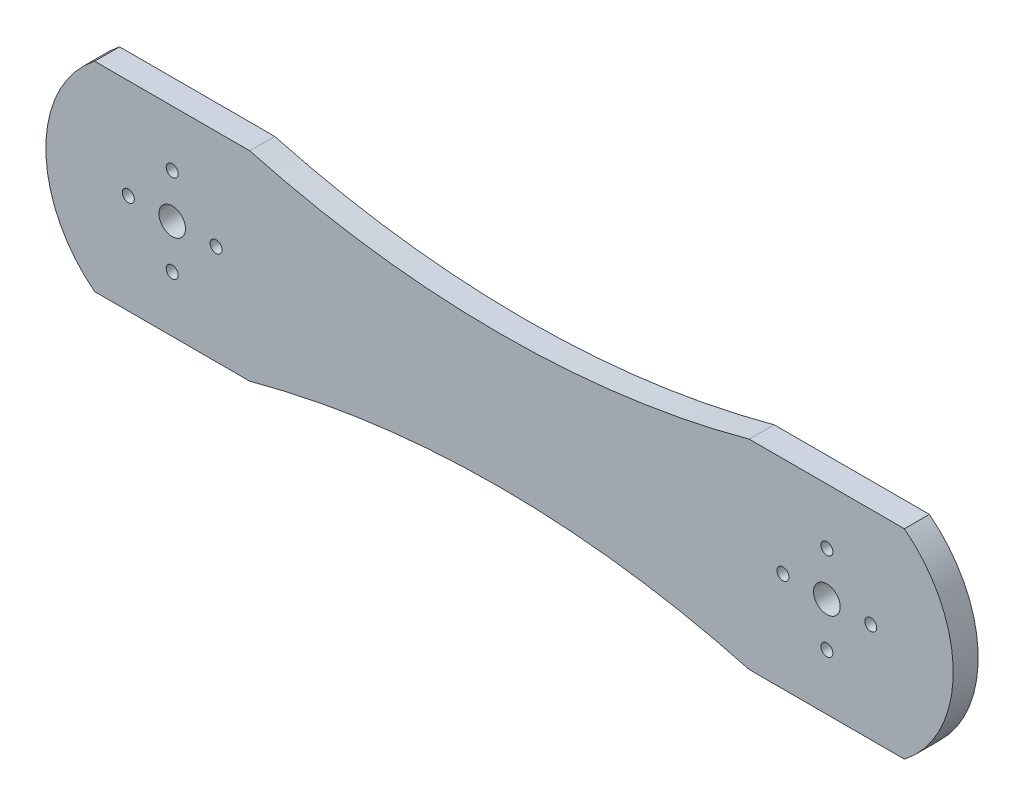
SolidWorks part; units mm, degrees
ref_plane "Front Plane" through (0, 0, 0) normal (0, 0, 1) x (1, 0, 0)
ref_plane "Top Plane" through (0, 0, 0) normal (0, 1, 0) x (1, 0, 0)
ref_plane "Right Plane" through (0, 0, 0) normal (1, 0, 0) x (0, 0, -1)
sketch "Sketch1" plane through (0, 0, 0) normal (0, 0, 1) x (1, 0, 0)
  line L0 (-77.3106, 19.05) -> (-47.6894, 19.05)
  line L1 (77.3106, -19.05) -> (47.6894, -19.05)
  line L2 (77.3106, 19.05) -> (-77.3106, -19.05) construction
  line L3 (-77.3106, 19.05) -> (-47.6894, -19.05) construction
  line L4 (47.6894, 19.05) -> (77.3106, 19.05)
  line L5 (0, -40.592) -> (0, 29.6436) construction
  line L6 (-47.6894, -19.05) -> (-77.3106, -19.05)
  arc A0 (-77.3106, 19.05) -> (-77.3106, -19.05) centre (-62.5, 0) ccw
  arc A1 (77.3106, -19.05) -> (77.3106, 19.05) centre (62.5, 0) ccw
  arc A4 (-47.6894, -19.05) -> (47.6894, -19.05) centre (0, -194.9519) cw
  arc A5 (-47.6894, 19.05) -> (47.6894, 19.05) centre (0, 194.9519) ccw
  point P3 (0, 0)
  point P12 (-62.5, 0)
  point P19 (0, 12.7)
  point P20 (0, -12.7)
  dimension "D3" = 24.13
  dimension "D1" = 38.1
  dimension "D2" = 125
  dimension "D5" = 25.4
extrude "Boss-Extrude1" add sketch "Sketch1" along normal blind 4.7625
sketch "Sketch2" plane through (0, 0, 4.7625) normal (0, 0, 1) x (1, 0, 0)
  circle A0 centre (-62.5, 0) radius 2.54
  circle A1 centre (-54.118, 0) radius 1.143
  circle A2 centre (-62.5, -8.382) radius 1.143
  circle A3 centre (-70.882, 0) radius 1.143
  circle A4 centre (-62.5, 8.382) radius 1.143
  arc A5 (-77.3106, 19.05) -> (-77.3106, -19.05) centre (-62.5, 0) ccw construction
  arc A6 (-77.3106, 19.05) -> (-77.3106, -19.05) centre (-62.5, 0) ccw construction
  arc A7 (77.3106, -19.05) -> (77.3106, 19.05) centre (62.5, 0) ccw construction
  arc A8 (77.3106, -19.05) -> (77.3106, 19.05) centre (62.5, 0) ccw construction
  circle A9 centre (62.5, 0) radius 2.54
  circle A10 centre (70.882, 0) radius 1.143
  circle A11 centre (62.5, -8.382) radius 1.143
  circle A12 centre (54.118, 0) radius 1.143
  circle A13 centre (62.5, 8.382) radius 1.143
  point P10 (-62.5, 0)
  point P19 (-62.5, 0)
  point P25 (62.5, 0)
  point P29 (62.5, 0)
  dimension "D1" = 5.08
  dimension "D2" = 2.286
  dimension "D3" = 8.382
  dimension "D5" = 2
  dimension "D4" = 4
extrude "Cut-Extrude1" cut sketch "Sketch2" against normal through all
